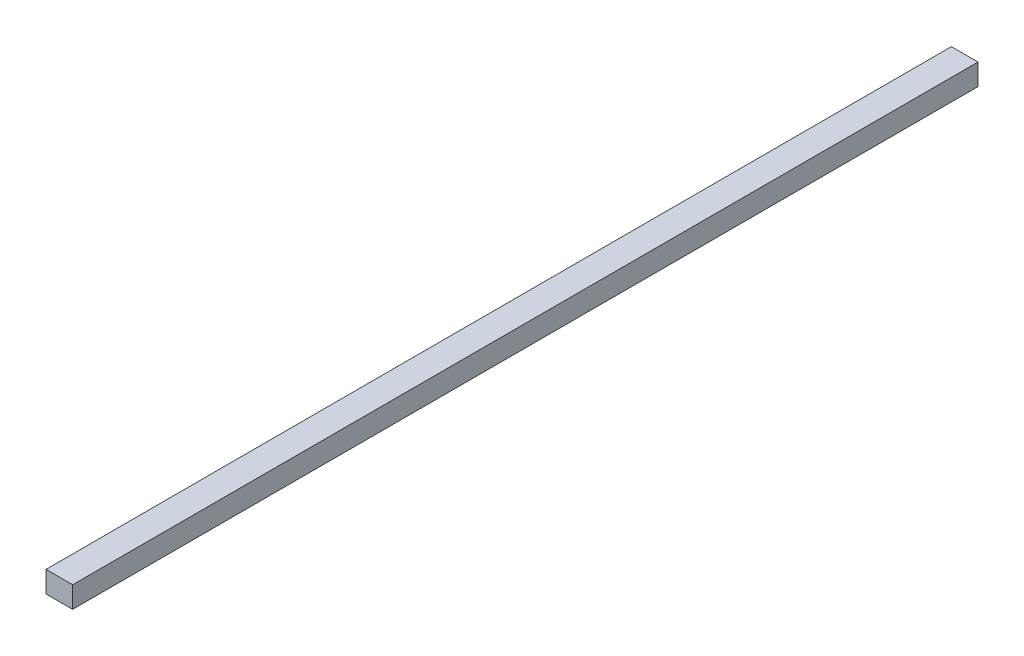
SolidWorks part; units mm, degrees
ref_plane "前基準面" through (0, 0, 0) normal (0, 0, 1) x (1, 0, 0)
ref_plane "上基準面" through (0, 0, 0) normal (0, 1, 0) x (1, 0, 0)
ref_plane "右基準面" through (0, 0, 0) normal (1, 0, 0) x (0, 0, -1)
sketch "草圖1" plane through (0, 0, 0) normal (0, 0, 1) x (1, 0, 0)
  line L1 (-5, 4) -> (5, 4)
  line L2 (-5, 4) -> (-5, -4)
  line L3 (-5, -4) -> (5, -4)
  line L4 (5, 4) -> (5, -4)
  point P4 (0, 4)
  point P6 (-5, 0)
  dimension "D1" = 10
  dimension "D2" = 8
extrude "填料-伸長1" add sketch "草圖1" along normal blind 340
sketch "草圖2" plane through (0, -4, 0) normal (0, -1, 0) x (1, 0, 0)
  line L0 (0, 0) -> (0, 340) construction
  line L1 (-5, 340) -> (5, 340) construction
sketch "草圖3" plane through (0, 4, 0) normal (0, 1, 0) x (1, 0, 0)
  line L0 (0, 0) -> (0, -340) construction
